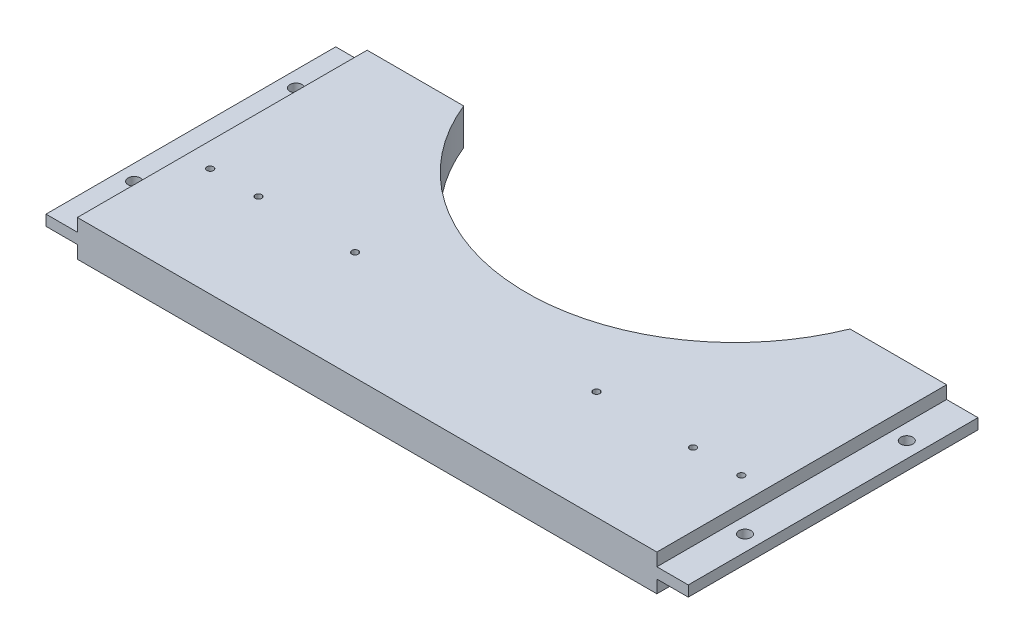
SolidWorks part; units mm, degrees
ref_plane "Front" through (0, 0, 0) normal (0, 0, 1) x (1, 0, 0)
ref_plane "Top" through (0, 0, 0) normal (0, 1, 0) x (1, 0, 0)
ref_plane "Right" through (0, 0, 0) normal (1, 0, 0) x (0, 0, -1)
sketch "Sketch1" plane through (0, 0, 0) normal (0, 1, 0) x (1, 0, 0)
  line L0 (-101.6, 76.2) -> (-152.4, 76.2)
  line L5 (-152.4, 76.2) -> (-152.4, -76.2)
  line L6 (-152.4, -76.2) -> (152.4, -76.2)
  line L7 (152.4, -76.2) -> (152.4, 76.2)
  line L8 (152.4, 76.2) -> (101.6, 76.2)
  line L9 (0, -50) -> (0, 50) construction
  line L10 (-24.4982, 7.62) -> (79.6476, 7.62) construction
  line L11 (-50, 0) -> (50, 0) construction
  circle A0 centre (0, 117.1693) radius 109.5493
  point P5 (152.4, 0)
  point P11 (0, -76.2)
  point P14 (0, 91.4312)
  point P17 (-133.2284, 76.2)
  dimension "D1" = 152.4
  dimension "D2" = 83.82
  dimension "D3" = 50.8
  dimension "D4" = 304.8
extrude "Boss-Extrude1" add sketch "Sketch1" along normal mid plane 19.05 contours L5 L10 A0 L0 | L10 L5 L6 L7 | A0 L10 L7 L8
sketch "Sketch2" plane through (0, 9.525, 0) normal (0, 1, 0) x (1, 0, 0)
  line L0 (-152.4, -19.05) -> (152.4, -19.05) construction
  line L1 (-152.4, 76.2) -> (-152.4, -76.2) construction
  line L2 (152.4, -76.2) -> (152.4, 76.2) construction
  line L3 (-152.4, -76.2) -> (152.4, -76.2) construction
  point P8 (-139.7, -19.05)
  point P9 (-114.3, -19.05)
  point P10 (-63.5, -19.05)
  point P12 (0, 0)
  dimension "D1" = 57.15
  dimension "D2" = 12.7
  dimension "D3" = 25.4
  dimension "D4" = 50.8
hole_wizard "#8-32 Tapped Hole1" positions "Sketch3" profile "Sketch5" tap size "#8-32" standard "ANSI Inch" end condition through all
sketch "Sketch3" plane through (0, 9.525, 0) normal (0, 1, 0) x (1, 0, 0)
  point P0 (-139.7, -19.05)
  point P3 (-114.3, -19.05)
  point P6 (-63.5, -19.05)
sketch "Sketch5" plane through (-139.7, 9.525, 19.05) normal (1, 0, 0) x (0, 0, 1)
  line L0 (0, 0) -> (0, 19.05)
  line L1 (0, 19.05) -> (1.7272, 19.05)
  line L2 (1.7272, 19.05) -> (1.7272, 0)
  line L5 (1.7272, 0) -> (0, 0)
  line L11 (0, -6.35) -> (0, 107.95) construction
  dimension "Thru Tap Drill Dia." = 3.4544
  dimension "Thru Tap Drill Depth" = 19.05
cosmetic thread "Hole Thread1" parameters "D2"=4.1656
cosmetic thread "Hole Thread2" parameters "D2"=4.1656
cosmetic thread "Hole Thread3" parameters "D2"=4.1656
mirror "Mirror1" about plane through (0, 0, 0) normal (1, 0, 0) of "#8-32 Tapped Hole1"
cosmetic thread "Hole Thread4" parameters "D2"=4.1656
cosmetic thread "Hole Thread5" parameters "D2"=4.1656
cosmetic thread "Hole Thread6" parameters "D2"=4.1656
sketch "Sketch6" plane through (0, 0, 0) normal (0, 1, 0) x (1, 0, 0)
  line L0 (-152.4, -76.2) -> (152.4, -76.2) construction
  line L1 (-152.4, 76.2) -> (-168.91, 76.2)
  line L2 (-152.4, 76.2) -> (-152.4, -76.2)
  line L3 (-152.4, -76.2) -> (-168.91, -76.2)
  line L4 (-168.91, 76.2) -> (-168.91, -76.2)
  dimension "D1" = 16.51
extrude "Boss-Extrude2" add sketch "Sketch6" along normal mid plane 5.588
sketch "Sketch7" plane through (0, 2.794, 0) normal (0, 1, 0) x (1, 0, 0)
  line L0 (-160.655, 76.2) -> (-160.655, -76.2) construction
  line L1 (-152.4, 76.2) -> (-168.91, 76.2) construction
  line L2 (-168.91, -76.2) -> (-152.4, -76.2) construction
  point P0 (-160.655, 46.99)
  point P1 (-160.655, -38.1)
  point P8 (0, 0)
  point P9 (0, 0)
  dimension "D1" = 29.21
  dimension "D2" = 38.1
hole_wizard "1/4 (0.25) Diameter Hole1" positions "Sketch8" profile "Sketch10" hole size "1/4" standard "ANSI Inch" end condition through all
sketch "Sketch8" plane through (0, 2.794, 0) normal (0, 1, 0) x (1, 0, 0)
  point P0 (-160.655, 46.99)
  point P3 (-160.655, -38.1)
sketch "Sketch10" plane through (-160.655, 2.794, -46.99) normal (1, 0, 0) x (0, 0, 1)
  line L0 (0, 0) -> (0, 12.319)
  line L1 (0, 12.319) -> (3.175, 12.319)
  line L2 (3.175, 12.319) -> (3.175, 0)
  line L5 (3.175, 0) -> (0, 0)
  line L11 (0, -6.35) -> (0, 107.95) construction
  dimension "Thru Hole Dia." = 6.35
  dimension "Thru Hole Depth" = 12.319
mirror "Mirror2" about plane through (0, 0, 0) normal (1, 0, 0) of "1/4 (0.25) Diameter Hole1", "Boss-Extrude2"
